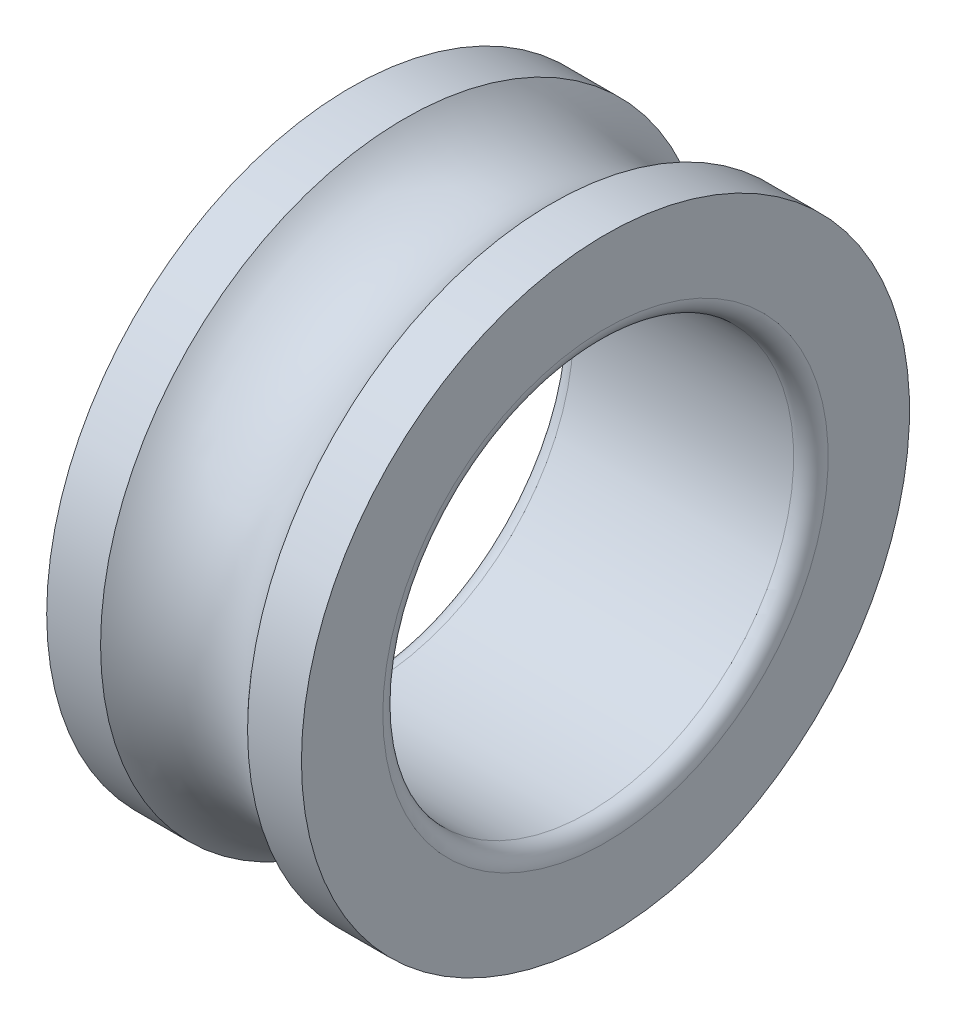
SolidWorks part; units mm, degrees
ref_plane "Front Plane" through (0, 0, 0) normal (0, 0, 1) x (1, 0, 0)
ref_plane "Top Plane" through (0, 0, 0) normal (0, 1, 0) x (1, 0, 0)
ref_plane "Right Plane" through (0, 0, 0) normal (1, 0, 0) x (0, 0, -1)
sketch "Sketch1" plane through (0, 0, 0) normal (0, 0, 1) x (1, 0, 0)
  line L0 (-26.756, 0) -> (39.8571, 0) construction
  line L1 (0, 0) -> (0, 83.6815) construction
  line L2 (-15.5, 37) -> (-8.9443, 37)
  line L3 (-15.5, 37) -> (-15.5, 27.1)
  line L4 (-13.4, 25) -> (13.4, 25)
  line L5 (15.5, 37) -> (15.5, 27.1)
  line L6 (-15.5, 37) -> (15.5, 25) construction
  line L7 (-15.5, 25) -> (15.5, 37) construction
  line L8 (8.9443, 37) -> (15.5, 37)
  arc A0 (8.9443, 37) -> (-8.9443, 37) centre (0, 45) cw
  arc A1 (13.4, 25) -> (15.5, 27.1) centre (13.4, 27.1) ccw
  arc A2 (-15.5, 27.1) -> (-13.4, 25) centre (-13.4, 27.1) ccw
  point P3 (0, 31)
  dimension "D5" = 12
  dimension "D6" = 2.1
  dimension "D1" = 31
  dimension "D2" = 25
  dimension "D3" = 37
  dimension "D4" = 8
revolve "Revolve1" add sketch "Sketch1" angle 360 about L0
